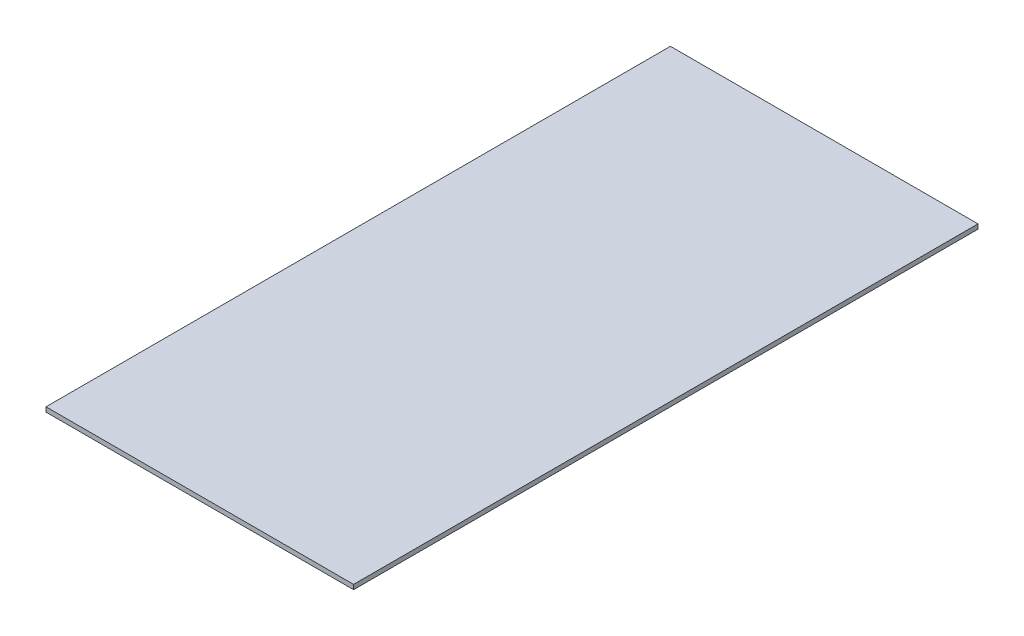
SolidWorks part; units mm, degrees
ref_plane "Front Plane" through (0, 0, 0) normal (0, 0, 1) x (1, 0, 0)
ref_plane "Top Plane" through (0, 0, 0) normal (0, 1, 0) x (1, 0, 0)
ref_plane "Right Plane" through (0, 0, 0) normal (1, 0, 0) x (0, 0, -1)
sketch "Sketch1" plane through (0, 0, 0) normal (0, 1, 0) x (1, 0, 0)
  line L1 (-100, -203) -> (100, -203)
  line L2 (-100, -203) -> (-100, 203)
  line L3 (-100, 203) -> (100, 203)
  line L4 (100, -203) -> (100, 203)
  line L5 (-100, -203) -> (100, 203) construction
  line L6 (-100, 203) -> (100, -203) construction
  point P0 (0, 0)
  dimension "D1" = 406
  dimension "D2" = 200
extrude "Boss-Extrude1" add sketch "Sketch1" along normal blind 3
